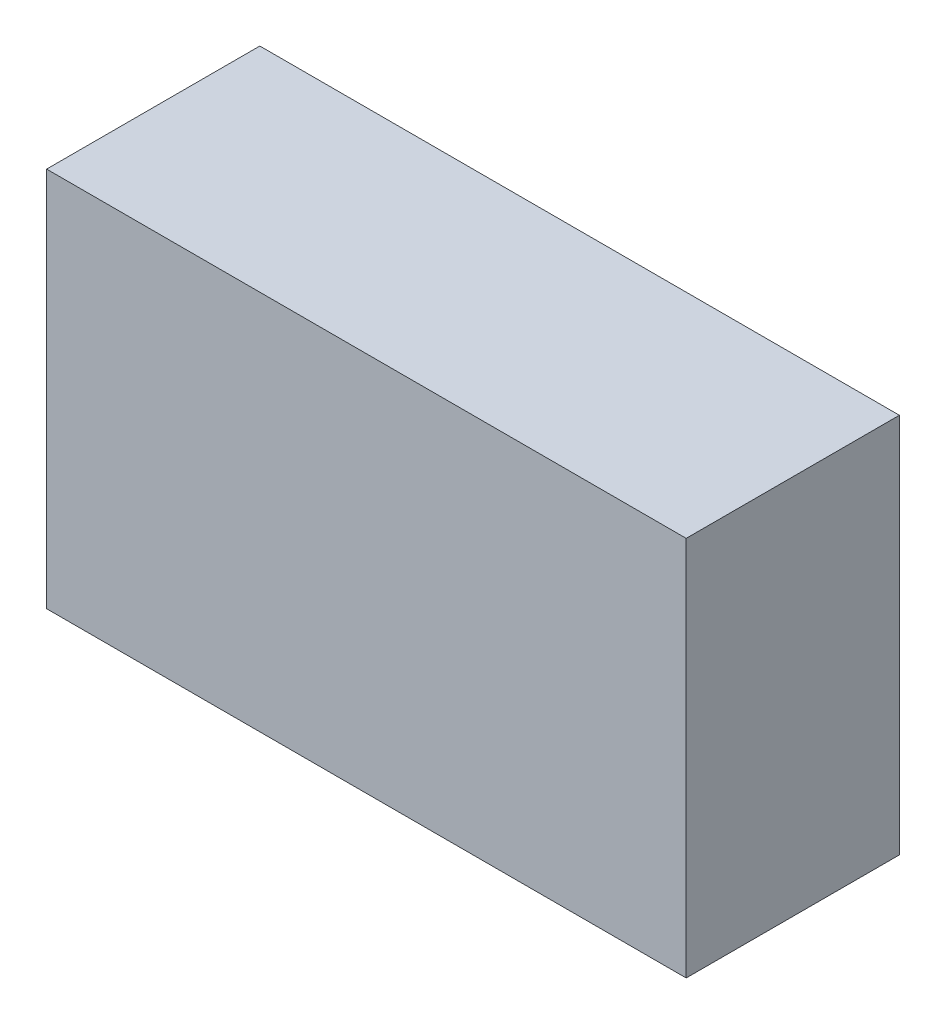
SolidWorks part; units mm, degrees
ref_plane "Front Plane" through (0, 0, 0) normal (0, 0, 1) x (1, 0, 0)
ref_plane "Top Plane" through (0, 0, 0) normal (0, 1, 0) x (1, 0, 0)
ref_plane "Right Plane" through (0, 0, 0) normal (1, 0, 0) x (0, 0, -1)
sketch "Sketch1" plane through (0, 0, 0) normal (1, 0, 0) x (0, 0, -1)
  line L1 (0, 0) -> (-50, 0)
  line L2 (0, 0) -> (0, -89.3)
  line L3 (0, -89.3) -> (-50, -89.3)
  line L4 (-50, 0) -> (-50, -89.3)
  dimension "D1" = 89.3
  dimension "D2" = 50
extrude "Boss-Extrude1" add sketch "Sketch1" along normal mid plane 150
